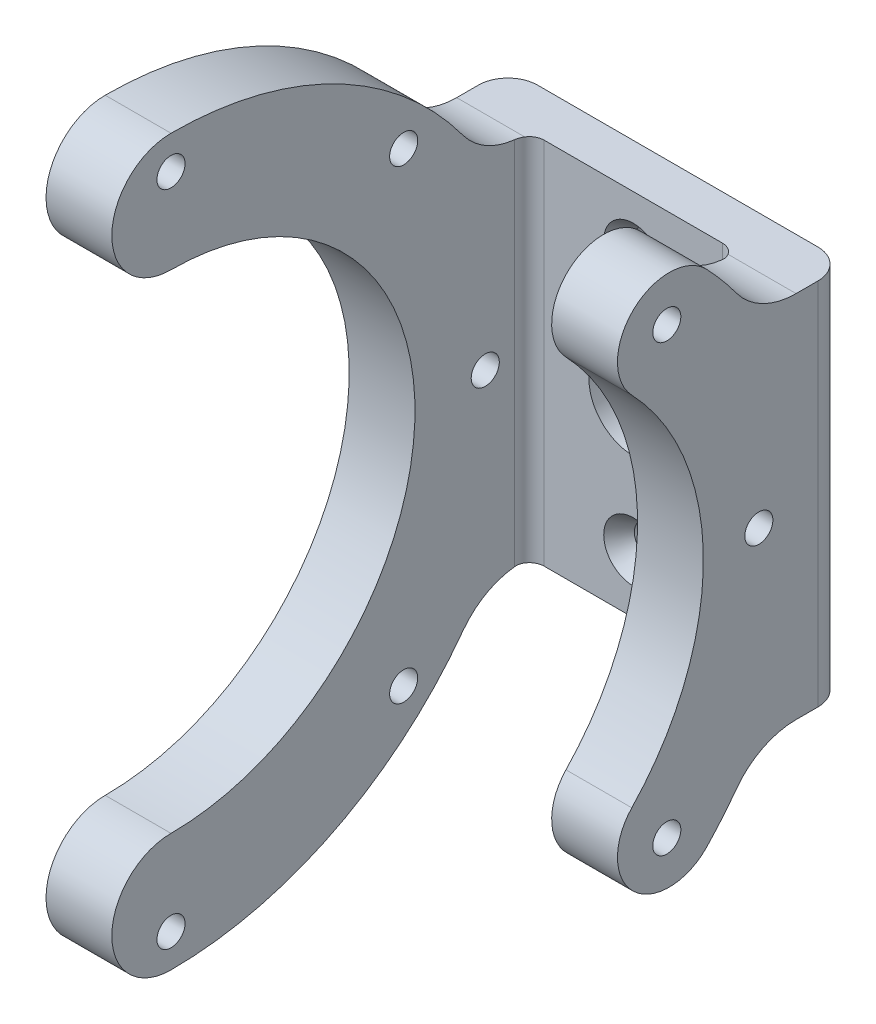
SolidWorks part; units mm, degrees
ref_plane "前视基准面" through (0, 0, 0) normal (0, 0, 1) x (1, 0, 0)
ref_plane "上视基准面" through (0, 0, 0) normal (0, 1, 0) x (1, 0, 0)
ref_plane "右视基准面" through (0, 0, 0) normal (1, 0, 0) x (0, 0, -1)
other "Configuration Table"
sketch "草图1" plane through (0, 0, 0) normal (0, 0, 1) x (1, 0, 0)
  line L0 (0, -24.95) -> (45.9, -24.95) construction
  line L1 (0, 0) -> (45.9, 0)
  line L2 (0, 0) -> (0, -49.9)
  line L3 (0, -49.9) -> (45.9, -49.9)
  line L4 (45.9, 0) -> (45.9, -49.9)
  line L5 (22.95, 0) -> (22.95, -49.9) construction
  dimension "D1" = 45.9
  dimension "D2" = 49.9
extrude "凸台-拉伸1" add sketch "草图1" along normal blind 6
sketch "草图2" plane through (45.9, 0, 0) normal (1, 0, 0) x (0, 0, -1)
  line L0 (0, -24.95) -> (-59.4722, -24.95) construction
  line L1 (-17.3, 0) -> (-6, 0)
  line L2 (-6, -49.9) -> (-17.3, -49.9)
  line L4 (0, -49.9) -> (0, 0)
  line L5 (0, 0) -> (-6, 0)
  line L6 (-6, 0) -> (-6, -49.9)
  line L7 (-6, -49.9) -> (0, -49.9)
  line L8 (0, -49.9) -> (0, 0)
  line L9 (0, 0) -> (-6, 0)
  line L10 (-6, 0) -> (-6, -49.9)
  line L11 (-6, -49.9) -> (0, -49.9)
  circle A0 centre (-59.4722, -24.95) radius 49
  circle A1 centre (-59.4722, -24.95) radius 35
  circle A2 centre (-59.4722, -24.95) radius 42.5 construction
  circle A3 centre (-16.9722, -24.95) radius 1.9
  circle A4 centre (-29.4202, -55.002) radius 1.9
  circle A5 centre (-59.4722, -67.45) radius 1.9
  circle A6 centre (-89.5243, -55.002) radius 1.9
  circle A7 centre (-101.9722, -24.95) radius 1.9
  circle A8 centre (-89.5243, 5.102) radius 1.9
  circle A9 centre (-59.4722, 17.55) radius 1.9
  circle A10 centre (-29.4202, 5.102) radius 1.9
  circle A11 centre (-29.0913, -53.95) radius 7
  circle A12 centre (-29.0913, 4.05) radius 7
  point P30 (-59.4722, -24.95)
  line M22 (-6, 0) -> (-6, -49.9)
  dimension "D2" = 17.3
  dimension "D3" = 98
  dimension "D4" = 70
  dimension "D5" = 85
  dimension "D6" = 3.8
  dimension "D8" = 45
  dimension "D9" = 58
  dimension "D1" = 0
  dimension "D7" = 8
extrude "凸台-拉伸2" add sketch "草图2" against normal blind 8.9 contours A12 A1 A11 A0 A3 | A0 L2 L1 M22 | A12 A10 | A11 A4
sketch "草图3" plane through (0, 0, 0) normal (-1, 0, 0) x (0, 0, 1)
  line L0 (0, -24.95) -> (59.4722, -24.95) construction
  line L1 (17.3, -49.9) -> (0, -49.9)
  line L4 (0, 0) -> (0, -49.9)
  line L5 (0, -49.9) -> (6, -49.9)
  line L6 (6, -49.9) -> (6, 0)
  line L7 (6, 0) -> (0, 0)
  line L8 (0, 0) -> (0, -49.9)
  line L9 (0, -49.9) -> (6, -49.9)
  line L10 (6, -49.9) -> (6, 0)
  line L11 (17.3, 0) -> (0, 0)
  circle A0 centre (59.4722, -24.95) radius 49
  circle A1 centre (59.4722, -24.95) radius 44.5 construction
  circle A2 centre (59.4722, -24.95) radius 42.5 construction
  circle A3 centre (59.4722, -24.95) radius 33
  circle A4 centre (16.9722, -24.95) radius 1.9
  circle A5 centre (14.9722, -24.95) radius 1.9
  circle A6 centre (28.006, 6.5163) radius 1.9
  circle A7 centre (29.4202, 5.102) radius 1.9
  circle A8 centre (59.4722, 19.55) radius 1.9
  circle A9 centre (59.4722, 17.55) radius 1.9
  circle A10 centre (90.9385, 6.5163) radius 1.9
  circle A11 centre (89.5243, 5.102) radius 1.9
  circle A12 centre (103.9722, -24.95) radius 1.9
  circle A13 centre (101.9722, -24.95) radius 1.9
  circle A14 centre (90.9385, -56.4163) radius 1.9
  circle A15 centre (89.5243, -55.002) radius 1.9
  circle A16 centre (59.4722, -69.45) radius 1.9
  circle A17 centre (59.4722, -67.45) radius 1.9
  circle A18 centre (28.006, -56.4163) radius 1.9
  circle A19 centre (29.4202, -55.002) radius 1.9
  circle A20 centre (96.7818, -7.95) radius 8
  circle A21 centre (96.7818, -41.95) radius 8
  point P45 (59.4722, -24.95)
  line M28 (6, -49.9) -> (6, 0)
  dimension "D2" = 98
  dimension "D3" = 89
  dimension "D4" = 85
  dimension "D5" = 66
  dimension "D6" = 3.8
  dimension "D7" = 3.8
  dimension "D9" = 17.3
  dimension "D11" = 34
  dimension "D10" = 45
  dimension "D1" = 0
  dimension "D8" = 8
extrude "凸台-拉伸3" add sketch "草图3" against normal blind 8.9 contours A0 L11 L1 M28 | A21 A3 A20 A0 A19 A18 A17 A16 A15 A14 A11 A10 A9 A8 A7 A6 A5 A4 | A20 | A21 | A4 A5 | A6 A7 | A18 A19 | A16 A17 | A14 A15 | A10 A11 | A8 A9
fillet "圆角3" radius 10 4 edges at (41.45, -49.9, 17.3) (4.45, -49.9, 17.3) (41.45, 0, 17.3) (4.45, 0, 17.3)
sketch "草图6" plane through (0, 0, 0) normal (-1, 0, 0) x (0, 0, 1)
  line L0 (4, -24.95) -> (26.4722, -24.95) construction
  line L3 (11.9381, 0) -> (0, 0)
  line L4 (0, 0) -> (0, -49.9)
  line L5 (0, -49.9) -> (11.9381, -49.9)
  line L6 (11.9381, 0) -> (0, 0)
  line L8 (0, -49.9) -> (11.9381, -49.9)
  line L10 (0, 0) -> (0, -49.9)
  circle A0 centre (59.4722, 16.05) radius 8
  circle A1 centre (59.4722, -65.95) radius 8
  arc A7 (104.0617, -4.6329) -> (19.9947, 4.0763) centre (59.4722, -24.95) ccw
  arc A8 (11.9381, 0) -> (19.9947, 4.0763) centre (11.9381, 10) ccw
  arc A9 (19.9947, -53.9763) -> (11.9381, -49.9) centre (11.9381, -59.9) ccw
  arc A10 (19.9947, -53.9763) -> (104.0617, -45.2671) centre (59.4722, -24.95) ccw
  arc A11 (104.0617, -45.2671) -> (89.5018, -38.6329) centre (96.7818, -41.95) ccw
  arc A12 (89.5018, -11.2671) -> (89.5018, -38.6329) centre (59.4722, -24.95) ccw
  arc A13 (89.5018, -11.2671) -> (104.0617, -4.6329) centre (96.7818, -7.95) ccw
  arc A14 (104.0617, -4.6329) -> (19.9947, 4.0763) centre (59.4722, -24.95) ccw
  arc A15 (11.9381, 0) -> (19.9947, 4.0763) centre (11.9381, 10) ccw
  arc A16 (19.9947, -53.9763) -> (11.9381, -49.9) centre (11.9381, -59.9) ccw
  arc A17 (19.9947, -53.9763) -> (104.0617, -45.2671) centre (59.4722, -24.95) ccw
  arc A18 (104.0617, -45.2671) -> (89.5018, -38.6329) centre (96.7818, -41.95) ccw
  arc A19 (89.5018, -11.2671) -> (89.5018, -38.6329) centre (59.4722, -24.95) ccw
  arc A20 (89.5018, -11.2671) -> (104.0617, -4.6329) centre (96.7818, -7.95) ccw
  arc M14 (104.0617, -4.6329) -> (19.9947, 4.0763) centre (59.4722, -24.95) ccw
  arc M20 (19.9947, -53.9763) -> (104.0617, -45.2671) centre (59.4722, -24.95) ccw
  arc M21 (104.0617, -45.2671) -> (89.5018, -38.6329) centre (96.7818, -41.95) ccw
  arc M22 (89.5018, -38.6329) -> (89.5018, -11.2671) centre (59.4722, -24.95) cw
  arc M23 (89.5018, -11.2671) -> (104.0617, -4.6329) centre (96.7818, -7.95) ccw
  circle M26 centre (90.9385, -56.4163) radius 1.9
  circle M27 centre (90.9385, 6.5163) radius 1.9
  dimension "D2" = 82
  dimension "D1" = 0
extrude "切除-拉伸2" cut sketch "草图6" against normal blind 10 contours A0 M22 M23 M14 M27 | A1 M20 M21 M22 M26
sketch "草图7" plane through (0, 0, 0) normal (0, 0, -1) x (-1, 0, 0)
  line L4 (0, -49.9) -> (0, 0)
  line L5 (0, 0) -> (-45.9, 0)
  line L6 (-45.9, 0) -> (-45.9, -49.9)
  line L7 (-45.9, -49.9) -> (0, -49.9)
  line L8 (0, -49.9) -> (0, 0)
  line L9 (0, 0) -> (-45.9, 0)
  line L10 (-45.9, 0) -> (-45.9, -49.9)
  line L11 (-45.9, -49.9) -> (0, -49.9)
  dimension "D1" = 0
extrude "切除-拉伸3" cut sketch "草图7" against normal blind 5
fillet "圆角4" radius 4 2 edges at (45.9, -24.95, 5) (0, -24.95, 5)
sketch "草图8" plane through (0, 0, 6) normal (0, 0, 1) x (1, 0, 0)
  line L4 (37, 0) -> (8.9, 0)
  line L5 (8.9, 0) -> (8.9, -49.9)
  line L6 (8.9, -49.9) -> (37, -49.9)
  line L7 (37, -49.9) -> (37, 0)
  line L8 (37, 0) -> (8.9, 0)
  line L9 (8.9, 0) -> (8.9, -49.9)
  line L10 (8.9, -49.9) -> (37, -49.9)
  line L11 (37, -49.9) -> (37, 0)
  dimension "D1" = 0
extrude "凸台-拉伸5" add sketch "草图8" along normal blind 5
fillet "圆角5" radius 2 2 edges at (37, -24.95, 11) (8.9, -24.95, 11)
sketch "草图11" plane through (0, 0, 11) normal (0, 0, 1) x (1, 0, 0)
  line L0 (22.95, 0) -> (22.95, -49.9) construction
  line L1 (10.9, -24.95) -> (35, -24.95) construction
  line L4 (10.9, -49.9) -> (35, -49.9)
  line L5 (35, -49.9) -> (35, 0)
  line L6 (35, 0) -> (10.9, 0)
  line L7 (10.9, 0) -> (10.9, -49.9)
  line L8 (10.9, -49.9) -> (35, -49.9)
  line L9 (35, -49.9) -> (35, 0)
  line L10 (35, 0) -> (10.9, 0)
  line L11 (10.9, 0) -> (10.9, -49.9)
  circle A0 centre (22.95, -24.95) radius 17.25 construction
  circle A1 centre (22.95, -7.7) radius 2.25
  circle A2 centre (22.95, -42.2) radius 2.25
  dimension "D2" = 34.5
  dimension "D3" = 4.5
  dimension "D1" = 0
extrude "切除-拉伸4" cut sketch "草图11" against normal blind 31 contours A1 | A2
ref_axis "基准轴1" through (22.95, -7.7, 5) along (0, 0, 1)
ref_plane "基准面1" through (22.95, 0, 0) normal (-1, 0, 0) x (0, 0, 1)
sketch "草图4" plane through (0, 0, 6) normal (0, 0, 1) x (1, 0, 0)
  line L0 (22.95, 0) -> (22.95, -49.9)
  line L1 (37, 0) -> (8.9, 0) construction
  line L2 (8.9, -49.9) -> (37, -49.9) construction
  circle A0 centre (22.95, -24.95) radius 6
  dimension "D1" = 12
extrude "切除-拉伸1" cut sketch "草图4" against normal blind 70 and the other way blind 66 contours L0 A0 | L0 A0
sketch "草图12" plane through (22.95, 0, 0) normal (-1, 0, 0) x (0, 0, 1)
  line L0 (11, -9.95) -> (11, -5.45) construction
  line L1 (11, -9.95) -> (11, -5.45)
  line L2 (11, -7.7) -> (11, -3.7)
  line L3 (11, -3.7) -> (8.4, -5.6)
  line L4 (8.4, -5.6) -> (8.4, -7.7)
  line L5 (5, -7.7) -> (11, -7.7) construction
  line L6 (8.4, -7.7) -> (11, -7.7)
  dimension "D1" = 2.6
  dimension "D2" = 4
  dimension "D3" = 2.1
revolve "切除-旋转1" cut sketch "草图12" angle 360 about axis through (22.95, -7.7, 5) along (0, 0, 1)
ref_plane "基准面2" through (0, -24.95, 0) normal (0, 1, 0) x (1, 0, 0)
mirror "镜向2" about plane through (0, -24.95, 0) normal (0, 1, 0) of "切除-旋转1"
